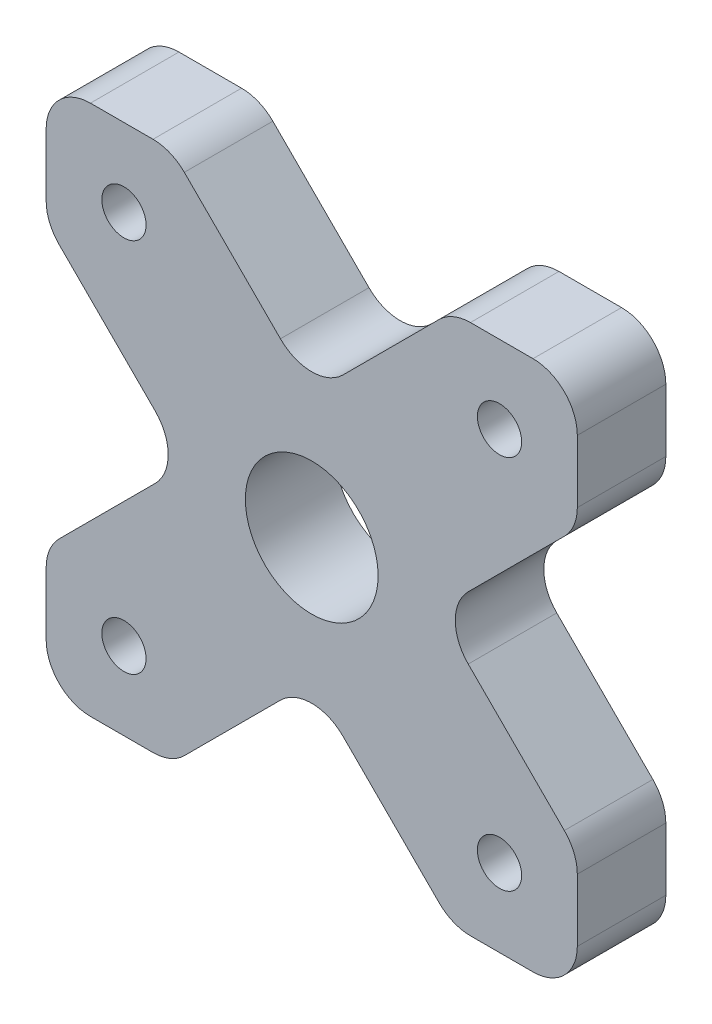
SolidWorks part; units mm, degrees
material "201 Annealed Stainless Steel (SS)"
ref_plane "Front Plane" through (0, 0, 0) normal (0, 0, 1) x (1, 0, 0)
ref_plane "Top Plane" through (0, 0, 0) normal (0, 1, 0) x (1, 0, 0)
ref_plane "Right Plane" through (0, 0, 0) normal (1, 0, 0) x (0, 0, -1)
sketch "Sketch1" plane through (0, 0, 0) normal (0, 0, 1) x (1, 0, 0)
  line L0 (17.9289, 30) -> (25, 30)
  line L1 (-25, -30) -> (-17.9289, -30)
  line L2 (-30, -25) -> (-30, -17.9289)
  line L3 (-25, 30) -> (-17.9289, 30)
  line L4 (30, -25) -> (30, -17.9289)
  line L5 (-30, -30) -> (30, 30) construction
  line L6 (-30, 30) -> (30, -30) construction
  line L7 (-30, 17.9289) -> (-30, 25)
  line L8 (-14.3934, -28.5355) -> (-3.5355, -17.6777)
  line L9 (-28.5355, -14.3934) -> (-17.6777, -3.5355)
  line L10 (-28.5355, 14.3934) -> (-17.6777, 3.5355)
  line L11 (-14.3934, 28.5355) -> (-3.5355, 17.6777)
  line L12 (3.5355, 17.6777) -> (14.3934, 28.5355)
  line L13 (17.9289, -30) -> (25, -30)
  line L14 (30, 17.9289) -> (30, 25)
  line L15 (17.6777, 3.5355) -> (28.5355, 14.3934)
  line L17 (17.6777, -3.5355) -> (28.5355, -14.3934)
  line L19 (3.5355, -17.6777) -> (14.3934, -28.5355)
  arc A0 (-30, -17.9289) -> (-28.5355, -14.3934) centre (-25, -17.9289) cw
  arc A1 (-17.9289, -30) -> (-14.3934, -28.5355) centre (-17.9289, -25) ccw
  arc A2 (17.9289, -30) -> (14.3934, -28.5355) centre (17.9289, -25) cw
  arc A3 (28.5355, -14.3934) -> (30, -17.9289) centre (25, -17.9289) cw
  arc A4 (30, 17.9289) -> (28.5355, 14.3934) centre (25, 17.9289) cw
  arc A5 (14.3934, 28.5355) -> (17.9289, 30) centre (17.9289, 25) cw
  arc A6 (-30, 17.9289) -> (-28.5355, 14.3934) centre (-25, 17.9289) ccw
  arc A7 (-14.3934, 28.5355) -> (-17.9289, 30) centre (-17.9289, 25) ccw
  arc A8 (-17.6777, -3.5355) -> (-17.6777, 3.5355) centre (-21.2132, 0) ccw
  arc A9 (17.6777, 3.5355) -> (17.6777, -3.5355) centre (21.2132, 0) ccw
  arc A10 (-3.5355, -17.6777) -> (3.5355, -17.6777) centre (0, -21.2132) cw
  arc A11 (3.5355, 17.6777) -> (-3.5355, 17.6777) centre (0, 21.2132) cw
  arc A12 (-25, -30) -> (-30, -25) centre (-25, -25) cw
  arc A13 (25, -30) -> (30, -25) centre (25, -25) ccw
  arc A14 (25, 30) -> (30, 25) centre (25, 25) cw
  arc A15 (-30, 25) -> (-25, 30) centre (-25, 25) cw
  circle A16 centre (-21.2132, 21.2132) radius 2.5
  circle A17 centre (21.2132, 21.2132) radius 2.5
  circle A18 centre (21.2132, -21.2132) radius 2.5
  circle A19 centre (-21.2132, -21.2132) radius 2.5
  circle A20 centre (0, 0) radius 7.5
  point P0 (0, 0)
  point P6 (-17.9289, -32.0711)
  point P7 (32.0711, 17.9289)
  point P8 (-32.0711, -17.9289)
  point P9 (17.9289, 32.0711)
  point P10 (-32.0711, 17.9289)
  point P11 (17.9289, -32.0711)
  point P12 (-17.9289, 32.0711)
  point P13 (32.0711, -17.9289)
  point P38 (15.8579, 30)
  point P41 (-30, 15.8579)
  point P48 (14.1421, 0)
  point P51 (0, -14.1421)
  point P77 (0, 0)
  dimension "D7" = 5
  dimension "D8" = 5
  dimension "D11" = 15
  dimension "D1" = 60
  dimension "D2" = 10
  dimension "D3" = 10
  dimension "D4" = 10
  dimension "D5" = 10
  dimension "D6" = 60
  dimension "D9" = 30
  dimension "D10" = 4
extrude "Boss-Extrude1" add sketch "Sketch1" along normal blind 10
